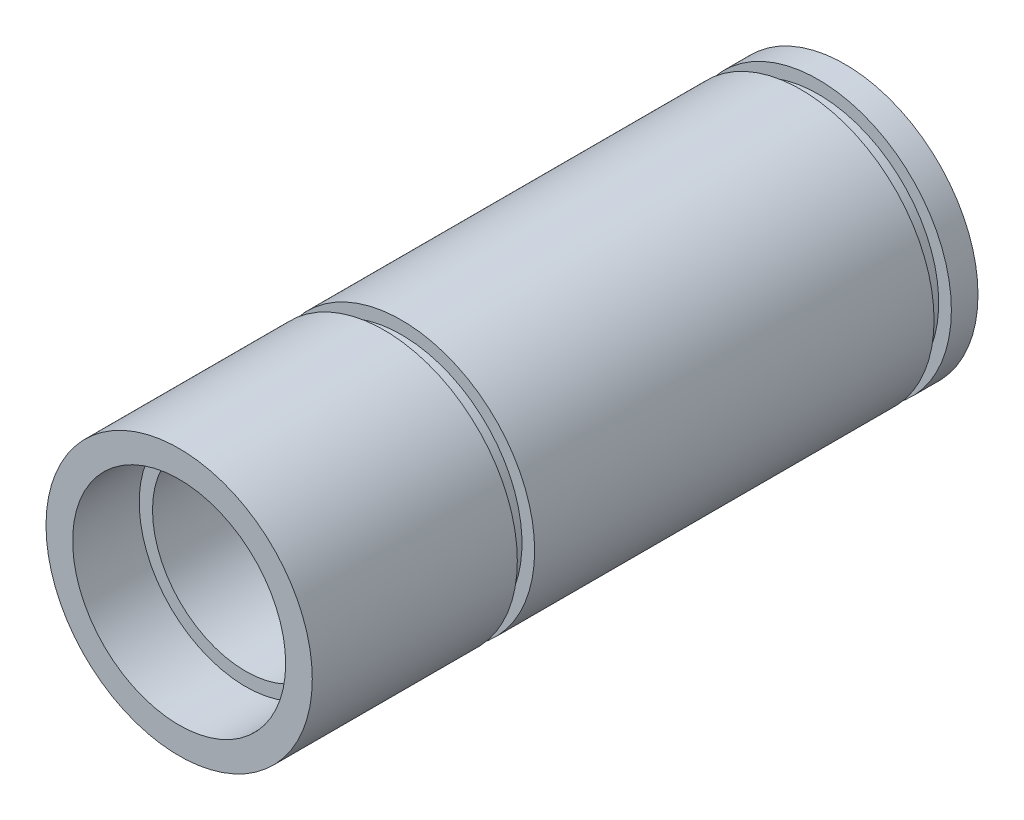
SolidWorks part; units mm, degrees
material "Plain Carbon Steel"
ref_plane "Front Plane" through (0, 0, 0) normal (0, 0, 1) x (1, 0, 0)
ref_plane "Top Plane" through (0, 0, 0) normal (0, 1, 0) x (1, 0, 0)
ref_plane "Right Plane" through (0, 0, 0) normal (1, 0, 0) x (0, 0, -1)
sketch "Sketch1" plane through (0, 0, 0) normal (0, 0, 1) x (1, 0, 0)
  circle A0 centre (0, 0) radius 7
  circle A1 centre (0, 0) radius 10
  dimension "D1" = 14
  dimension "D2" = 20
extrude "Main" add sketch "Sketch1" along normal blind 50
sketch "Sketch2" plane through (0, 0, 50) normal (0, 0, 1) x (1, 0, 0)
  circle A0 centre (0, 0) radius 8
  dimension "D1" = 16
extrude "Bearing Cut" cut sketch "Sketch2" against normal blind 5
ref_plane "Plane1" through (0, 0, 25) normal (0, 0, 1) x (1, 0, 0)
mirror "Mirror1" about plane through (0, 0, 25) normal (0, 0, 1) of "Bearing Cut"
ref_plane "Plane2" through (0, 0, 2) normal (0, 0, -1) x (-1, 0, 0)
sketch "Sketch5" plane through (0, 0, 2) normal (0, 0, -1) x (-1, 0, 0)
  circle A0 centre (0, 0) radius 9.05
  circle A1 centre (0, 0) radius 10
  dimension "D1" = 18.1
  dimension "D2" = 20
extrude "Cut-Extrude2" cut sketch "Sketch5" along direction (0, 0, 1) on the side against the normal blind 1.3 contours A1 | A0
ref_plane "Plane3" through (0, 0, 33.3) normal (0, 0, -1) x (-1, 0, 0)
sketch "Sketch6" plane through (0, 0, 33.3) normal (0, 0, -1) x (-1, 0, 0)
  circle A0 centre (0, 0) radius 10
  circle A1 centre (0, 0) radius 9.05
  dimension "D1" = 20
  dimension "D2" = 18.1
extrude "Cut-Extrude3" cut sketch "Sketch6" against normal blind 1.3
